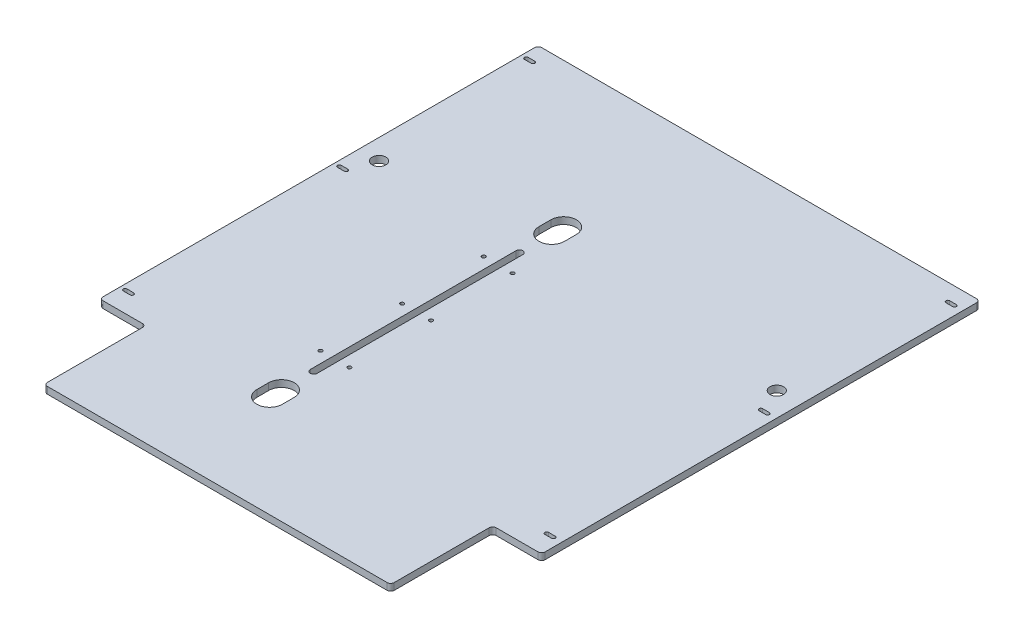
SolidWorks part; units mm, degrees
material "PE High Density"
ref_plane "Front" through (0, 0, 0) normal (0, 0, 1) x (1, 0, 0)
ref_plane "Top" through (0, 0, 0) normal (0, 1, 0) x (1, 0, 0)
ref_plane "Right" through (0, 0, 0) normal (1, 0, 0) x (0, 0, -1)
sketch "Sketch1" plane through (0, 0, 0) normal (0, 1, 0) x (1, 0, 0)
  line L0 (0, 0) -> (96.0438, 0)
  line L1 (96.0438, 0) -> (96.0438, -190.5)
  line L2 (96.0438, -190.5) -> (743.7437, -190.5)
  line L3 (743.7437, -190.5) -> (743.7437, 0)
  line L4 (743.7437, 0) -> (838.2, 0)
  line L5 (838.2, 0) -> (838.2, 819.15)
  line L6 (838.2, 819.15) -> (0, 819.15)
  line L7 (0, 819.15) -> (0, 0)
  line L8 (25.4, 0) -> (25.4, 819.15) construction
  line L9 (19.05, 38.1) -> (31.75, 38.1) construction
  line L10 (19.05, 41.4782) -> (31.75, 41.4782)
  line L11 (19.05, 34.7218) -> (31.75, 34.7218)
  line L12 (19.05, 438.15) -> (31.75, 438.15) construction
  line L13 (19.05, 441.5282) -> (31.75, 441.5282)
  line L14 (19.05, 434.7718) -> (31.75, 434.7718)
  line L15 (31.75, 787.4) -> (19.05, 787.4) construction
  line L16 (31.75, 784.0218) -> (19.05, 784.0218)
  line L17 (31.75, 790.7782) -> (19.05, 790.7782)
  line L18 (419.8937, 819.15) -> (419.8938, -190.5) construction
  line L19 (812.8, 787.4) -> (812.8, 438.15) construction
  line L20 (806.45, 787.4) -> (819.15, 787.4) construction
  line L21 (806.45, 784.0218) -> (819.15, 784.0218)
  line L22 (806.45, 790.7782) -> (819.15, 790.7782)
  line L23 (819.15, 438.15) -> (806.45, 438.15) construction
  line L24 (819.15, 441.5282) -> (806.45, 441.5282)
  line L25 (819.15, 434.7718) -> (806.45, 434.7718)
  line L26 (819.15, 38.1) -> (806.45, 38.1) construction
  line L27 (819.15, 41.4782) -> (806.45, 41.4782)
  line L28 (819.15, 34.7218) -> (806.45, 34.7218)
  line L29 (419.8938, -190.5) -> (419.8937, 819.15) construction
  line L30 (812.8, 438.15) -> (812.8, 38.1) construction
  arc A1 (19.05, 41.4782) -> (19.05, 34.7218) centre (19.05, 38.1) ccw
  arc A2 (31.75, 34.7218) -> (31.75, 41.4782) centre (31.75, 38.1) ccw
  arc A3 (19.05, 441.5282) -> (19.05, 434.7718) centre (19.05, 438.15) ccw
  arc A4 (31.75, 434.7718) -> (31.75, 441.5282) centre (31.75, 438.15) ccw
  arc A5 (31.75, 784.0218) -> (31.75, 790.7782) centre (31.75, 787.4) ccw
  arc A6 (19.05, 790.7782) -> (19.05, 784.0218) centre (19.05, 787.4) ccw
  arc A7 (806.45, 784.0218) -> (806.45, 790.7782) centre (806.45, 787.4) cw
  arc A8 (819.15, 790.7782) -> (819.15, 784.0218) centre (819.15, 787.4) cw
  arc A9 (819.15, 441.5282) -> (819.15, 434.7718) centre (819.15, 438.15) cw
  arc A10 (806.45, 434.7718) -> (806.45, 441.5282) centre (806.45, 438.15) cw
  arc A11 (819.15, 41.4782) -> (819.15, 34.7218) centre (819.15, 38.1) cw
  arc A12 (806.45, 34.7218) -> (806.45, 41.4782) centre (806.45, 38.1) cw
  point P13 (25.4, 38.1)
  point P20 (25.4, 438.15)
  point P27 (25.4, 787.4)
  point P38 (812.8, 787.4)
  point P45 (812.8, 438.15)
  point P52 (812.8, 38.1)
  dimension "D2" = 96.0438
  dimension "D3" = 819.15
  dimension "D4" = 25.4
  dimension "D5" = 6.7564
  dimension "D6" = 38.1
  dimension "D7" = 12.7
  dimension "D8" = 400.05
  dimension "D9" = 349.25
  dimension "D10" = 190.5
  dimension "D11" = 647.7
  dimension "D12" = 25.4
  dimension "D13" = 94.4562
extrude "Boss-Extrude1" add sketch "Sketch1" along normal blind 12.7
fillet "Fillet1" radius 6.604 2 edges at (96.0438, 6.35, 0) (743.7437, 6.35, 0)
fillet "Fillet2" radius 6.604 6 edges at (0, 6.35, -819.15) (838.2, 6.35, -819.15) (838.2, 6.35, 0) (743.7437, 6.35, 190.5) (0, 6.35, 0) (96.0438, 6.35, 190.5)
sketch "Sketch2" plane through (0, 12.7, 0) normal (0, 1, 0) x (1, 0, 0)
  line L0 (838.2, 6.604) -> (838.2, 812.546) construction
  line L1 (838.2, 6.604) -> (838.2, 812.546) construction
  line L3 (806.45, 438.15) -> (819.15, 438.15) construction
  line L5 (838.2, 483.87) -> (47.625, 483.87) construction
  line L6 (0, 812.546) -> (0, 6.604) construction
  circle A6 centre (47.625, 483.87) radius 12.7
  circle A7 centre (790.575, 483.87) radius 12.7
  dimension "D1" = 45.72
  dimension "D2" = 25.4
  dimension "D3" = 47.625
  dimension "D4" = 47.625
extrude "Cut-Extrude1" cut sketch "Sketch2" against normal through all
sketch "Sketch4" plane through (0, 0, 0) normal (0, -1, 0) x (1, 0, 0)
  line L0 (0, -812.546) -> (0, -6.604) construction
  line L3 (327.025, -527.05) -> (327.025, -549.275) construction
  line L4 (350.8375, -527.05) -> (350.8375, -549.275)
  line L5 (303.2125, -527.05) -> (303.2125, -549.275)
  line L7 (831.596, -819.15) -> (6.604, -819.15) construction
  line L8 (327.025, 0) -> (327.025, -22.225) construction
  line L9 (350.8375, 0) -> (350.8375, -22.225)
  line L10 (303.2125, 0) -> (303.2125, -22.225)
  circle A0 centre (327.025, -538.1625) radius 28.575 construction
  arc A2 (350.8375, -527.05) -> (303.2125, -527.05) centre (327.025, -527.05) ccw
  arc A3 (303.2125, -549.275) -> (350.8375, -549.275) centre (327.025, -549.275) ccw
  arc A4 (350.8375, 0) -> (303.2125, 0) centre (327.025, 0) ccw
  arc A5 (303.2125, -22.225) -> (350.8375, -22.225) centre (327.025, -22.225) ccw
  point P8 (327.025, -11.1125)
  point P12 (327.025, -538.1625)
  dimension "D2" = 57.15
  dimension "D1" = 327.025
  dimension "D3" = 527.05
  dimension "D4" = 47.625
  dimension "D5" = 22.225
  dimension "D6" = 280.9875
extrude "Cut-Extrude3" cut sketch "Sketch4" against normal through all
sketch "Sketch5" plane through (0, 0, 0) normal (0, -1, 0) x (1, 0, 0)
  line L0 (327.025, -22.225) -> (327.025, -527.05) construction
  line L1 (327.025, -466.725) -> (327.025, -82.55) construction
  line L2 (320.675, -466.725) -> (320.675, -82.55)
  line L3 (333.375, -466.725) -> (333.375, -82.55)
  arc A0 (320.675, -466.725) -> (333.375, -466.725) centre (327.025, -466.725) ccw
  arc A1 (333.375, -82.55) -> (320.675, -82.55) centre (327.025, -82.55) ccw
  point P6 (327.025, -274.6375)
  dimension "D1" = 384.175
  dimension "D2" = 12.7
extrude "Cut-Extrude4" cut sketch "Sketch5" against normal through all
sketch "Sketch6" plane through (0, 0, 0) normal (0, -1, 0) x (1, 0, 0)
  line L0 (327.025, -82.55) -> (327.025, -466.725) construction
  line L1 (327.025, -274.6375) -> (354.0125, -274.6375) construction
  line L2 (354.0125, -122.2375) -> (354.0125, -427.0375) construction
  line L3 (300.0375, -122.2375) -> (300.0375, -427.0375) construction
  circle A0 centre (354.0125, -274.6375) radius 3.3782
  circle A1 centre (354.0125, -427.0375) radius 3.3782
  circle A2 centre (354.0125, -122.2375) radius 3.3782
  circle A3 centre (300.0375, -427.0375) radius 3.3782
  circle A4 centre (300.0375, -274.6375) radius 3.3782
  circle A5 centre (300.0375, -122.2375) radius 3.3782
  dimension "D2" = 6.7564
  dimension "D1" = 26.9875
  dimension "D3" = 152.4
extrude "Cut-Extrude5" cut sketch "Sketch6" against normal through all
sketch "Sketch7" plane through (0, 0, 0) normal (0, -1, 0) x (1, 0, 0)
  line L0 (838.2, -6.604) -> (838.2, -812.546) construction
  line L1 (0, -812.546) -> (0, -6.604) construction
  line L2 (838.2, -6.604) -> (838.2, -812.546)
  line L3 (0, -812.546) -> (0, -6.604)
  line L4 (9.525, -812.546) -> (9.525, -6.604)
  line L5 (835.025, -6.604) -> (835.025, -812.546)
  line L6 (828.421, 0) -> (831.596, 0)
  line L7 (831.596, -819.15) -> (828.421, -819.15)
  line L8 (16.129, -819.15) -> (6.604, -819.15)
  line L9 (16.129, 0) -> (6.604, 0)
  arc A0 (831.596, -819.15) -> (838.2, -812.546) centre (831.596, -812.546) ccw construction
  arc A1 (838.2, -6.604) -> (831.596, 0) centre (831.596, -6.604) ccw construction
  arc A2 (6.604, 0) -> (0, -6.604) centre (6.604, -6.604) ccw construction
  arc A3 (0, -812.546) -> (6.604, -819.15) centre (6.604, -812.546) ccw construction
  arc A4 (831.596, -819.15) -> (838.2, -812.546) centre (831.596, -812.546) ccw
  arc A5 (838.2, -6.604) -> (831.596, 0) centre (831.596, -6.604) ccw
  arc A6 (6.604, 0) -> (0, -6.604) centre (6.604, -6.604) ccw
  arc A7 (0, -812.546) -> (6.604, -819.15) centre (6.604, -812.546) ccw
  arc A8 (16.129, 0) -> (9.525, -6.604) centre (16.129, -6.604) ccw
  arc A9 (9.525, -812.546) -> (16.129, -819.15) centre (16.129, -812.546) ccw
  arc A10 (828.421, -819.15) -> (835.025, -812.546) centre (828.421, -812.546) ccw
  arc A11 (835.025, -6.604) -> (828.421, 0) centre (828.421, -6.604) ccw
  dimension "D3" = 9.525
  dimension "D4" = 3.175
  dimension "D1" = 2
  dimension "D2" = 2
extrude "Cut-Extrude6" cut sketch "Sketch7" against normal through all contours A9 L4 A8 L9 A6 L3 A7 L8 | A11 L5 A10 L7 A4 L2 A5 L6
